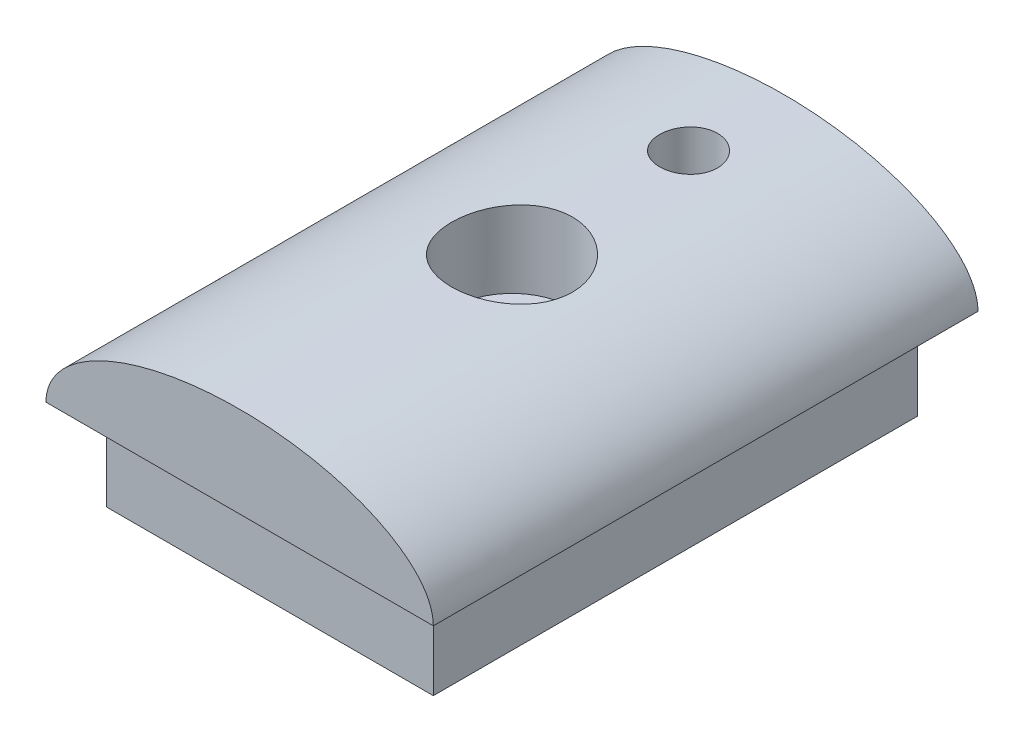
SolidWorks part; units mm, degrees
ref_plane "前视基准面" through (0, 0, 0) normal (0, 0, 1) x (1, 0, 0)
ref_plane "上视基准面" through (0, 0, 0) normal (0, 1, 0) x (1, 0, 0)
ref_plane "右视基准面" through (0, 0, 0) normal (1, 0, 0) x (0, 0, -1)
sketch "草图1" plane through (0, 0, 0) normal (0, 0, 1) x (1, 0, 0)
  line L0 (-69.1237, 0) -> (65.7328, 0) construction
  line L1 (0, 67.7524) -> (0, -70.0216) construction
  line L2 (-32, 0) -> (32, 0)
  ellipse E0 centre (0, 0) end of major axis (32, 0) minor radius 15 (32, 0) -> (-32, 0) ccw
  dimension "D1" = 30
  dimension "D2" = 64
extrude "凸台-拉伸1" add sketch "草图1" along normal blind 90
sketch "草图2" plane through (0, 0, 0) normal (0, -1, 0) x (1, 0, 0)
  line L0 (0, 90) -> (0, 0) construction
  line L1 (-32, 90) -> (32, 90) construction
  line L2 (-32, 45) -> (32, 45) construction
  line L3 (-32, 90) -> (-32, 0) construction
  line L4 (32, 90) -> (32, 0) construction
  line L6 (-27, 85) -> (27, 85)
  line L7 (-27, 85) -> (-27, 5)
  line L8 (-27, 5) -> (27, 5)
  line L9 (27, 85) -> (27, 5)
  line L10 (-27, 85) -> (27, 5) construction
  line L11 (-27, 5) -> (27, 85) construction
  line L12 (-24, 8) -> (24, 8)
  line L13 (-24, 8) -> (-24, 82)
  line L14 (-24, 82) -> (24, 82)
  line L15 (24, 8) -> (24, 82)
  line L16 (-24, 8) -> (24, 82) construction
  line L17 (-24, 82) -> (24, 8) construction
  point P11 (0, 45)
  point P16 (0, 45)
  dimension "D1" = 54
  dimension "D2" = 80
  dimension "D3" = 3
  dimension "D4" = 3
extrude "凸台-拉伸2" add sketch "草图2" along normal blind 15
ref_plane "基准面1" through (0, 0, 45) normal (0, 0, -1) x (-1, 0, 0)
sketch "草图3" plane through (0, -15, 0) normal (0, -1, 0) x (1, 0, 0)
  line L0 (-27, 5) -> (27, 5) construction
  line L1 (-24, 8) -> (24, 8)
  line L2 (-24, 8) -> (-24, 5)
  line L3 (-24, 5) -> (24, 5)
  line L4 (24, 8) -> (24, 5)
  line L5 (24, 8) -> (24, 82) construction
extrude "切除-拉伸1" cut sketch "草图3" against normal blind 5
sketch "草图4" plane through (27, 0, 0) normal (1, 0, 0) x (0, 0, -1)
  line L0 (-45, 0) -> (-45, -15) construction
  line L1 (-5, 0) -> (-85, 0) construction
  line L2 (-5, -15) -> (-85, -15) construction
  line L3 (-85, -6) -> (-5, -6) construction
  line L4 (-85, -15) -> (-85, 0) construction
  line L5 (-5, -15) -> (-5, 0) construction
  circle A0 centre (-52.5, -6) radius 1.75
  circle A1 centre (-72.5, -6) radius 1.75
  circle A2 centre (-32.5, -6) radius 1.75
  circle A3 centre (-12.5, -6) radius 1.75
  dimension "D2" = 3.5
  dimension "D1" = 6
  dimension "D3" = 12.5
  dimension "D4" = 4
sketch "草图5" plane through (0, 0, 82) normal (0, 0, -1) x (-1, 0, 0)
  line L0 (0, 9.6974) -> (0, -11.9255) construction
  line L1 (-18.4283, 0) -> (16.4738, 0) construction
  line L2 (32, 0) -> (-32, 0) construction
  line L3 (-24, -10) -> (-24, -15) construction
  ellipse E0 centre (0, 0) end of major axis (-24, 0) minor radius 8
  dimension "D1" = 8
extrude "切除-拉伸3" cut sketch "草图5" along normal up to surface (74 mm away) up to face at (0, -5, 8)
sketch "草图6" plane through (0, -15, 0) normal (0, -1, 0) x (1, 0, 0)
  line L0 (0, 82) -> (0, 19.5225) construction
  line L1 (-24, 82) -> (24, 82) construction
  line L3 (24, 8) -> (-24, 8) construction
  circle A0 centre (0, 13.5) radius 5.5
  dimension "D1" = 11
ref_plane "基准面2" through (0, 0, 0) normal (0, -1, 0) x (-1, 0, 0)
ref_plane "基准面3" through (0, 0, 0) normal (0, -1, 0) x (-1, 0, 0)
sketch "草图15" plane through (0, 0, 0) normal (0, -1, 0) x (-1, 0, 0)
  line L0 (0, 10.4018) -> (0, -101.7019) construction
  line L1 (-32, -45) -> (42.9057, -45) construction
  line L2 (-32, -90) -> (-32, 0) construction
  circle A0 centre (0, -45) radius 11
  dimension "D1" = 22
extrude "凸台-拉伸9" add sketch "草图15" against normal up to surface (15 mm away)
ref_plane "基准面4" through (0, 2, 0) normal (0, -1, 0) x (-1, 0, 0)
sketch "草图16" plane through (0, 2, 0) normal (0, -1, 0) x (-1, 0, 0)
  circle A0 centre (0, -45) radius 10
  circle A1 centre (0, -45) radius 11 construction
  dimension "D1" = 20
extrude "切除-拉伸4" cut sketch "草图16" against normal through all
sketch "草图17" plane through (0, 2, 0) normal (0, 1, 0) x (1, 0, 0)
  line L1 (0, -82) -> (0, -19.5225) construction
  line L2 (-6.5, -40) -> (-1.5, -40)
  line L3 (-6.5, -40) -> (-6.5, -50)
  line L4 (-6.5, -50) -> (-1.5, -50)
  line L5 (-1.5, -40) -> (-1.5, -50)
  line L6 (-6.5, -40) -> (-1.5, -50) construction
  line L7 (-6.5, -50) -> (-1.5, -40) construction
  line L8 (11.4427, -45) -> (-18.9487, -45) construction
  point P0 (-4, -45)
  dimension "D1" = 5
  dimension "D2" = 10
  dimension "D3" = 4
extrude "切除-拉伸6" cut sketch "草图17" against normal through all contours L2 L5 L4 L3
mirror "镜向1" about plane through (0, 0, 0) normal (1, 0, 0) of "切除-拉伸6"
scale "缩放比例1" scale about origin uniform scaling yes scale factor 1.2
sketch "草图18" plane through (0, 0, 0) normal (0, -1, 0) x (1, 0, 0)
  circle A0 centre (0, 19) radius 5.75
  dimension "D1" = 11.5
  dimension "D2" = 19
extrude "切除-拉伸7" cut sketch "草图18" against normal through all
